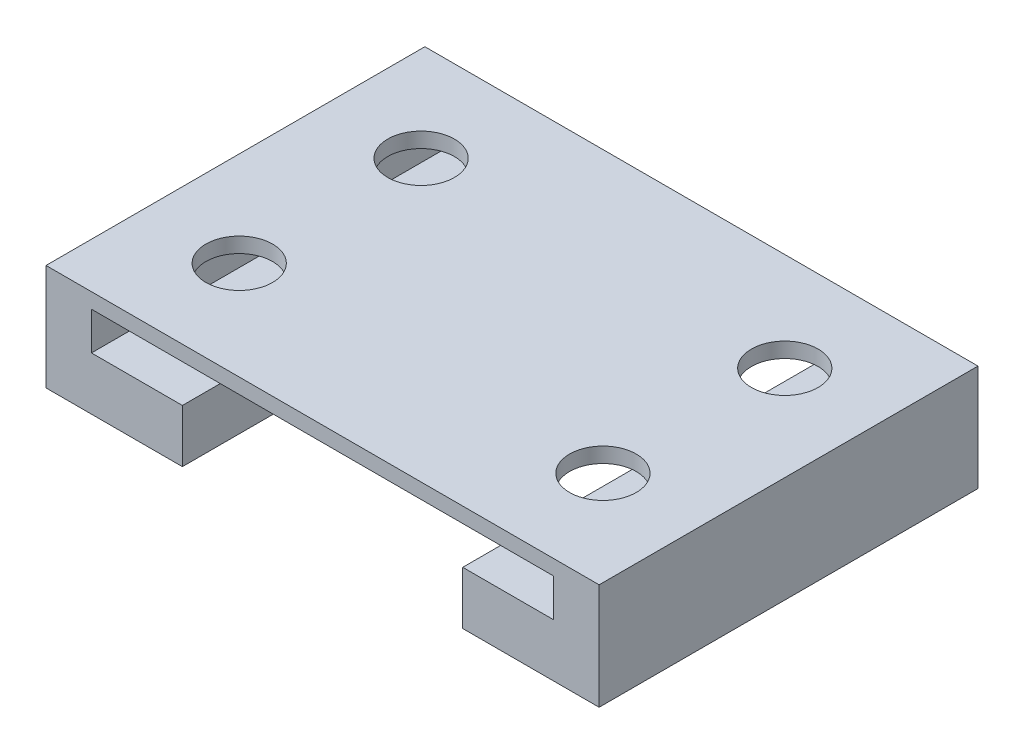
SolidWorks part; units mm, degrees
material "ABS"
ref_plane "Спереди" through (0, 0, 0) normal (0, 0, 1) x (1, 0, 0)
ref_plane "Сверху" through (0, 0, 0) normal (0, 1, 0) x (1, 0, 0)
ref_plane "Справа" through (0, 0, 0) normal (1, 0, 0) x (0, 0, -1)
sketch "Эскиз3" plane through (0, 0, 0) normal (0, 0, 1) x (1, 0, 0)
  line L0 (0, 36.404) -> (0, -21.66) construction
  line L1 (-9.25, 0) -> (-18.25, 0)
  line L2 (-18.25, 0) -> (-18.25, 7)
  line L3 (-18.25, 7) -> (18.25, 7)
  line L4 (18.25, 7) -> (18.25, 0)
  line L5 (18.25, 0) -> (9.25, 0)
  line L6 (9.25, 0) -> (9.25, 3.5)
  line L7 (9.25, 3.5) -> (15.25, 3.5)
  line L8 (15.25, 3.5) -> (15.25, 6)
  line L9 (15.25, 6) -> (-15.25, 6)
  line L10 (-15.25, 6) -> (-15.25, 3.5)
  line L11 (-15.25, 3.5) -> (-9.25, 3.5)
  line L12 (-9.25, 3.5) -> (-9.25, 0)
  dimension "D1" = 18.5
  dimension "D2" = 3.5
  dimension "D3" = 2.5
  dimension "D4" = 1
  dimension "D5" = 30.5
  dimension "D6" = 3
extrude "Бобышка-Вытянуть3" add sketch "Эскиз3" along normal mid plane 25
hole_wizard "Зенковка для винта с потайной головкой M21" positions "Эскиз5" profile "Эскиз4" countersink size "M2" standard "ISO" end condition through all
sketch "Эскиз5" plane through (0, 7, 0) normal (0, 1, 0) x (1, 0, 0)
  line L0 (-18.25, 0) -> (18.25, 0) construction
  line L1 (-18.25, -12.5) -> (-18.25, 12.5) construction
  line L2 (18.25, -12.5) -> (18.25, 12.5) construction
  line L4 (0, 12.5) -> (0, -12.5) construction
  line L5 (18.25, 12.5) -> (-18.25, 12.5) construction
  line L6 (18.25, -12.5) -> (-18.25, -12.5) construction
  point P0 (-12, 6)
  point P17 (-12, -6)
  point P19 (12, -6)
  point P20 (12, 6)
  dimension "D1" = 12
  dimension "D2" = 24
sketch "Эскиз4" plane through (-12, 7, -6) normal (1, 0, 0) x (0, 0, 1)
  line L0 (0, 0) -> (0, 7)
  line L1 (0, 7) -> (1.2, 7)
  line L2 (1.2, 7) -> (1.2, 1)
  line L3 (1.2, 1) -> (2.2, 0)
  line L5 (2.2, 0) -> (0, 0)
  line L6 (-1.2, 1) -> (-2.2, 0) construction
  line L11 (0, -6.35) -> (0, 107.95) construction
  dimension "Диаметр сквозного отверстия" = 2.4
  dimension "Глубина сквозного отверстия" = 7
  dimension "Диаметр передней зенковки" = 4.4
  dimension "Угол передней зенковки" = 90
sketch "Эскиз6" plane through (0, 7, 0) normal (0, 1, 0) x (1, 0, 0)
  circle A0 centre (-12, -6) radius 2.2 construction
  circle A1 centre (12, -6) radius 2.2 construction
  circle A2 centre (12, 6) radius 2.2 construction
  circle A3 centre (-12, 6) radius 2.2 construction
  circle A4 centre (-12, -6) radius 2.2
  circle A5 centre (12, -6) radius 2.2
  circle A6 centre (12, 6) radius 2.2
  circle A7 centre (-12, 6) radius 2.2
extrude "Вырез-Вытянуть1" cut sketch "Эскиз6" against normal up to next
sketch "Эскиз7" [suppressed] plane through (0, 6.2, 0) normal (0, 1, 0) x (1, 0, 0)
  line L1 (-9.25, -12.5) -> (9.25, -12.5)
  line L2 (-9.25, -12.5) -> (-9.25, -6)
  line L3 (-9.25, -6) -> (9.25, -6)
  line L4 (9.25, -12.5) -> (9.25, -6)
  line L5 (18.25, 12.5) -> (-18.25, 12.5) construction
  line L6 (-9.25, 12.5) -> (9.25, 12.5)
  line L7 (-9.25, 12.5) -> (-9.25, 6)
  line L8 (-9.25, 6) -> (9.25, 6)
  line L9 (9.25, 12.5) -> (9.25, 6)
  line L10 (18.25, -12.5) -> (-18.25, -12.5) construction
  line L11 (0, 0) -> (0, -6) construction
  dimension "D1" = 6.5
  dimension "D2" = 18.5
extrude "Вырез-Вытянуть2" [suppressed] cut sketch "Эскиз7" against normal up to surface (5.2 mm away)
fillet "Скругление1" [suppressed] radius 2
